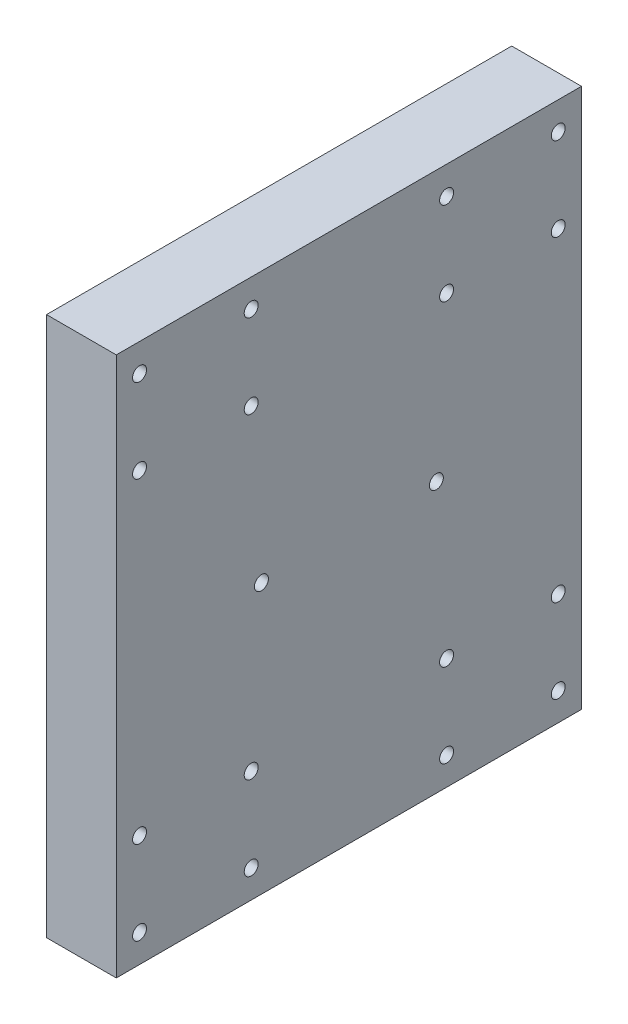
SolidWorks part; units mm, degrees
ref_plane "Alzado" through (0, 0, 0) normal (0, 0, 1) x (1, 0, 0)
ref_plane "Planta" through (0, 0, 0) normal (0, 1, 0) x (1, 0, 0)
ref_plane "Vista lateral" through (0, 0, 0) normal (1, 0, 0) x (0, 0, -1)
sketch "Croquis1" plane through (0, 0, 0) normal (1, 0, 0) x (0, 0, -1)
  line L0 (0, 58) -> (100, 58) construction
  line L1 (0, 0) -> (100, 0)
  line L2 (0, 0) -> (0, 116)
  line L3 (0, 116) -> (100, 116)
  line L4 (100, 0) -> (100, 116)
  line L5 (50, 116) -> (50, 0) construction
  circle A0 centre (5, 110) radius 1.5
  circle A1 centre (29, 110) radius 1.5
  circle A2 centre (5, 92) radius 1.5
  circle A3 centre (29, 92) radius 1.5
  circle A4 centre (5, 24) radius 1.5
  circle A5 centre (29, 24) radius 1.5
  circle A6 centre (29, 6) radius 1.5
  circle A7 centre (5, 6) radius 1.5
  circle A8 centre (31.2, 58) radius 1.5
  circle A9 centre (68.8, 58) radius 1.5
  circle A10 centre (71, 6) radius 1.5
  circle A11 centre (95, 6) radius 1.5
  circle A12 centre (95, 24) radius 1.5
  circle A13 centre (71, 24) radius 1.5
  circle A14 centre (95, 92) radius 1.5
  circle A15 centre (71, 92) radius 1.5
  circle A16 centre (71, 110) radius 1.5
  circle A17 centre (95, 110) radius 1.5
  dimension "D3" = 3
  dimension "D7" = 3
  dimension "D1" = 5
  dimension "D2" = 6
  dimension "D4" = 24
  dimension "D5" = 18
  dimension "D6" = 37.6
  dimension "D8" = 18.8
  dimension "D9" = 116
  dimension "D10" = 100
extrude "Saliente-Extruir1" add sketch "Croquis1" along normal blind 15
sketch "Croquis3" plane through (0, 0, 0) normal (-1, 0, 0) x (0, 0, 1)
  line L0 (-100, 58) -> (0, 58) construction
  line L1 (-100, 0) -> (-100, 116) construction
  line L2 (0, 116) -> (0, 0) construction
  line L3 (-46.5, 17) -> (-46.5, 58) construction
  line L4 (-46.5, 58) -> (-46.5, 99) construction
  line L5 (-100, 116) -> (0, 116) construction
  circle A0 centre (-46.5, 99) radius 11
  circle A1 centre (-46.5, 17) radius 11
  dimension "D1" = 22
  dimension "D2" = 17
  dimension "D3" = 46.5
  dimension "D4" = 53.5
extrude "Cortar-Extruir2" cut sketch "Croquis3" against normal blind 7
